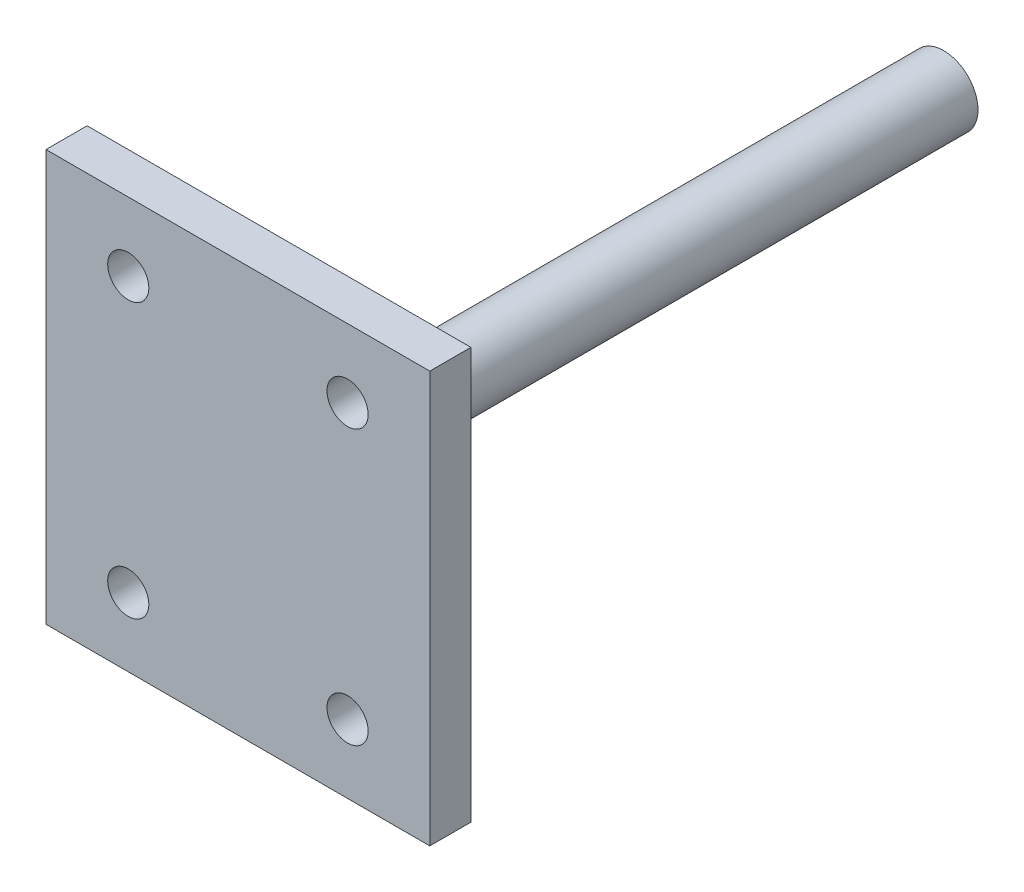
SolidWorks part; units mm, degrees
ref_plane "前视基准面" through (0, 0, 0) normal (0, 0, 1) x (1, 0, 0)
ref_plane "上视基准面" through (0, 0, 0) normal (0, 1, 0) x (1, 0, 0)
ref_plane "右视基准面" through (0, 0, 0) normal (1, 0, 0) x (0, 0, -1)
other "Configuration Table"
sketch "草图1" plane through (0, 0, 0) normal (0, 0, 1) x (1, 0, 0)
  line L1 (0, 0) -> (28, 0)
  line L2 (0, 0) -> (0, 30)
  line L3 (0, 30) -> (28, 30)
  line L4 (28, 0) -> (28, 30)
  dimension "D1" = 28
  dimension "D2" = 30
extrude "凸台-拉伸1" add sketch "草图1" along normal blind 3
sketch "草图2" plane through (0, 0, 3) normal (0, 0, 1) x (1, 0, 0)
  line L0 (0, 15) -> (50000, 15) construction
  line L1 (0, 30) -> (0, 0) construction
  line L2 (14, 30) -> (14, -49970) construction
  line L3 (28, 30) -> (0, 30) construction
  line L5 (6, 5) -> (22, 5) construction
  line L6 (6, 5) -> (6, 25) construction
  line L7 (6, 25) -> (22, 25) construction
  line L8 (22, 5) -> (22, 25) construction
  line L9 (6, 5) -> (22, 25) construction
  line L10 (6, 25) -> (22, 5) construction
  circle A0 centre (6, 25) radius 1.5
  circle A1 centre (22, 25) radius 1.5
  circle A2 centre (22, 5) radius 1.5
  circle A3 centre (6, 5) radius 1.5
  point P4 (0, 15)
  point P9 (14, 30)
  point P10 (14, 15)
  dimension "D3" = 3
  dimension "D4" = 3
  dimension "D5" = 3
  dimension "D6" = 3
  dimension "D1" = 16
  dimension "D2" = 20
extrude "切除-拉伸1" cut sketch "草图2" against normal up to next and the other way through all
sketch "草图3" plane through (0, 0, 0) normal (0, 0, -1) x (-1, 0, 0)
  line L0 (-28, 15) -> (49972, 15) construction
  line L1 (-28, 0) -> (-28, 30) construction
  line L2 (-14, 30) -> (-14, -49970) construction
  line L3 (-28, 30) -> (0, 30) construction
  circle A0 centre (-14, 15) radius 2.495
  point P4 (-28, 15)
  point P9 (-14, 30)
  dimension "D1" = 4.99
extrude "凸台-拉伸2" add sketch "草图3" along normal blind 48.5
